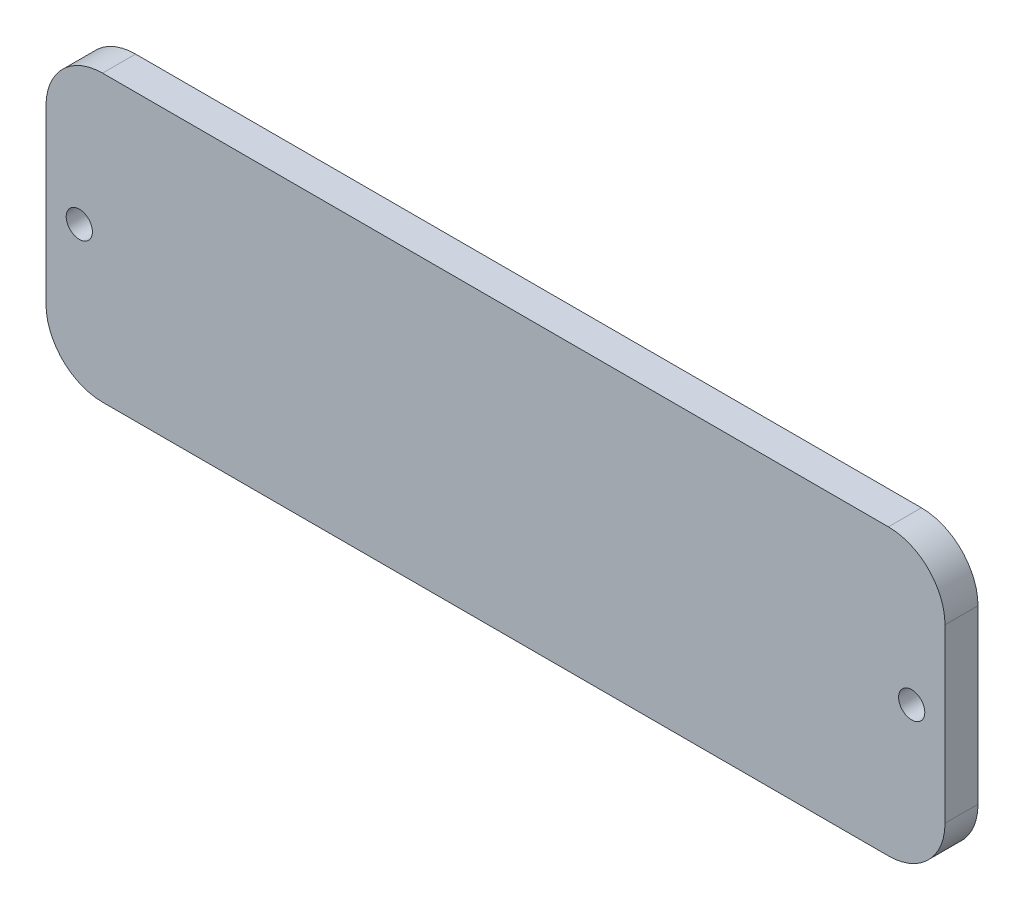
SolidWorks part; units mm, degrees
ref_plane "Front Plane" through (0, 0, 0) normal (0, 0, 1) x (1, 0, 0)
ref_plane "Top Plane" through (0, 0, 0) normal (0, 1, 0) x (1, 0, 0)
ref_plane "Right Plane" through (0, 0, 0) normal (1, 0, 0) x (0, 0, -1)
sketch "Sketch1" plane through (0, 0, -49.2125) normal (0, 0, -1) x (-1, 0, 0)
  line L20 (23.8125, 8.636) -> (-23.8125, 8.636)
  line L21 (-27.2415, 5.207) -> (-27.2415, -5.207)
  line L22 (-23.8125, -8.636) -> (23.8125, -8.636)
  line L23 (27.2415, -5.207) -> (27.2415, 5.207)
  line L24 (23.8125, 8.636) -> (-23.8125, 8.636)
  line L25 (-27.2415, 5.207) -> (-27.2415, -5.207)
  line L26 (-23.8125, -8.636) -> (23.8125, -8.636)
  line L27 (27.2415, -5.207) -> (27.2415, 5.207)
  arc A22 (-23.8125, 8.636) -> (-27.2415, 5.207) centre (-23.8125, 5.207) ccw
  arc A23 (-27.2415, -5.207) -> (-23.8125, -8.636) centre (-23.8125, -5.207) ccw
  arc A24 (23.8125, -8.636) -> (27.2415, -5.207) centre (23.8125, -5.207) ccw
  arc A26 (27.2415, 5.207) -> (23.8125, 8.636) centre (23.8125, 5.207) ccw
  arc A28 (-23.8125, 8.636) -> (-27.2415, 5.207) centre (-23.8125, 5.207) ccw
  arc A30 (-27.2415, -5.207) -> (-23.8125, -8.636) centre (-23.8125, -5.207) ccw
  arc A32 (23.8125, -8.636) -> (27.2415, -5.207) centre (23.8125, -5.207) ccw
  arc A34 (27.2415, 5.207) -> (23.8125, 8.636) centre (23.8125, 5.207) ccw
  dimension "D1" = 0.1905
extrude "Boss-Extrude1" add sketch "Sketch1" against normal blind 2
sketch "Sketch2" plane through (0, 0, -47.2125) normal (0, 0, 1) x (1, 0, 0)
  point P0 (25.223, 0)
  point P1 (-25.223, 0)
hole_wizard "1/16 (0.0625) Diameter Hole2" positions "3DSketch2" profile "Sketch4" hole size "1/16" standard "ANSI Inch"
sketch3d "3DSketch2"
  point P0 (25.223, 0, -47.2125)
  point P2 (-25.223, 0, -47.2125)
sketch "Sketch4" plane through (25.223, 0, -47.2125) normal (1, 0, 0) x (0, -1, 0)
  line L0 (0, 0) -> (0, 19.5269)
  line L1 (0, 19.5269) -> (0.7937, 19.05)
  line L2 (0.7937, 19.05) -> (0.7937, 0)
  line L5 (0.7937, 0) -> (0, 0)
  line L10 (0, 19.5269) -> (-0.7937, 19.05) construction
  line L11 (0, -6.35) -> (0, 107.95) construction
  dimension "Hole Dia." = 1.5875
  dimension "Hole Depth" = 19.05
  dimension "Drill Angle" = 118
